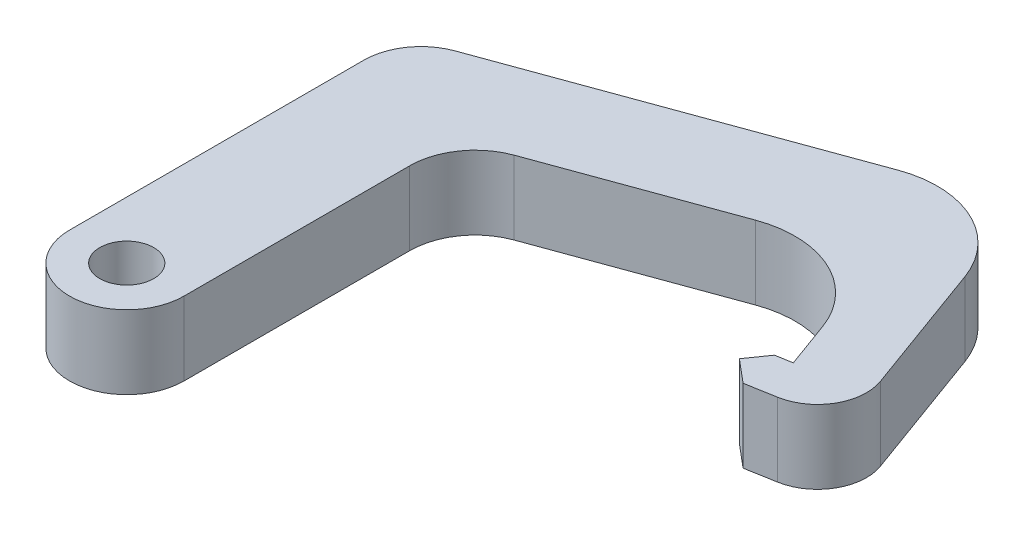
SolidWorks part; units mm, degrees
ref_plane "Front Plane" through (0, 0, 0) normal (0, 0, 1) x (1, 0, 0)
ref_plane "Top Plane" through (0, 0, 0) normal (0, 1, 0) x (1, 0, 0)
ref_plane "Right Plane" through (0, 0, 0) normal (1, 0, 0) x (0, 0, -1)
sketch "Sketch1" plane through (0, 0, 0) normal (0, 1, 0) x (1, 0, 0)
  line L0 (0, 0) -> (0, 18) construction
  line L1 (-3.5, 0) -> (-3.5, 18)
  line L2 (3.5, 0) -> (3.5, 18)
  line L3 (0, 18) -> (25.501, 27.2816) construction
  line L6 (-1.1971, 21.2889) -> (24.3039, 30.5705)
  line L7 (0, 0) -> (22.721, 14.5861) construction
  line L8 (22.5973, 23.5643) -> (25.6755, 15.1071)
  line L9 (24.3039, 30.5705) -> (30.5437, 13.4269)
  line L10 (22.5973, 23.5643) -> (3.1568, 16.4885)
  line L12 (30.5437, 13.4269) -> (25.221, 12.4884)
  line L14 (25.6755, 15.1071) -> (22.721, 14.5861)
  line L15 (25.221, 12.4884) -> (22.721, 14.5861)
  arc A0 (-3.5, 0) -> (3.5, 0) centre (0, 0) ccw
  arc A1 (3.5, 18) -> (-3.5, 18) centre (0, 18) ccw
  circle A4 centre (0, 0) radius 1.65
  point P3 (0, 9)
  dimension "D1" = 3.3
  dimension "D2" = 3.5
  dimension "D3" = 110
  dimension "D4" = 18
  dimension "D5" = 6
  dimension "D6" = 9
  dimension "D7" = 3
  dimension "D8" = 2.5
  dimension "D9" = 2.5
  dimension "D10" = 80
  dimension "D11" = 4
  dimension "D12" = 27
extrude "Boss-Extrude1" add sketch "Sketch1" along normal blind 4.5
fillet "Fillet1" radius 4 1 edges at (3.5, 2.25, -16.6135)
fillet "Fillet2" radius 6 2 edges at (24.3039, 2.25, -30.5705) (22.5973, 2.25, -23.5643)
fillet "Fillet3" radius 3 1 edges at (30.5437, 2.25, -13.4269)
chamfer "Chamfer1" distance 2 angle 45 1 edges at (22.721, 2.25, -14.5861)
